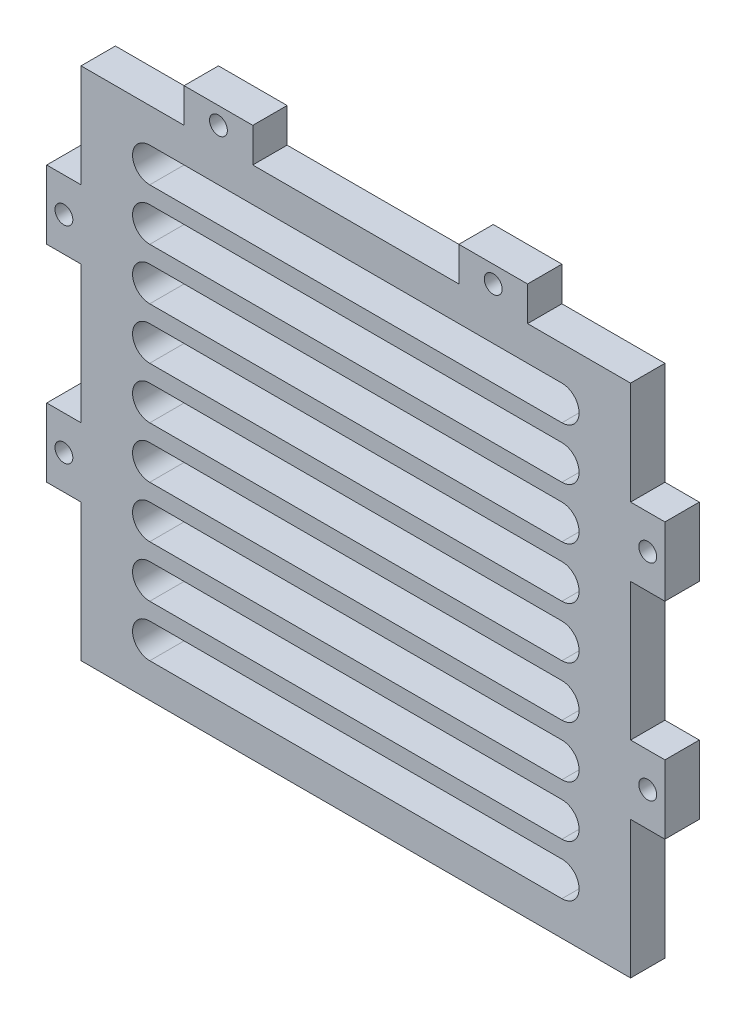
SolidWorks part; units mm, degrees
ref_plane "Front Plane" through (0, 0, 0) normal (0, 0, 1) x (1, 0, 0)
ref_plane "Top Plane" through (0, 0, 0) normal (0, 1, 0) x (1, 0, 0)
ref_plane "Right Plane" through (0, 0, 0) normal (1, 0, 0) x (0, 0, -1)
sketch "Sketch1" plane through (0, 0, 0) normal (0, 0, 1) x (1, 0, 0)
  line L1 (50.8, 39.9954) -> (-50.8, 39.9954)
  line L2 (50.8, 39.9954) -> (50.8, -55.2546)
  line L3 (50.8, -55.2546) -> (-50.8, -55.2546)
  line L4 (-50.8, 39.9954) -> (-50.8, -55.2546)
  line L5 (0, -55.2546) -> (0, 0) construction
  line L6 (50.8, -55.2546) -> (50.8, -29.8546) construction
  line L7 (-31.75, 39.9954) -> (-63.5, 39.9954) construction
  line L8 (-50.8, -55.2546) -> (-57.15, -55.2546) construction
extrude "Boss-Extrude1" add sketch "Sketch1" along normal blind 6.35
sketch "Sketch2" plane through (0, 0, 6.35) normal (0, 0, 1) x (1, 0, 0)
  line L0 (50.8, 39.9954) -> (-50.8, 39.9954) construction
  line L1 (-31.75, 39.9954) -> (-19.05, 39.9954)
  line L2 (-31.75, 39.9954) -> (-31.75, 46.3454)
  line L3 (-31.75, 46.3454) -> (-19.05, 46.3454)
  line L4 (-19.05, 39.9954) -> (-19.05, 46.3454)
  line L5 (-19.05, 43.1704) -> (19.05, 43.1704) construction
  line L6 (19.05, 39.9954) -> (31.75, 39.9954)
  line L7 (19.05, 39.9954) -> (19.05, 46.3454)
  line L8 (19.05, 46.3454) -> (31.75, 46.3454)
  line L9 (31.75, 39.9954) -> (31.75, 46.3454)
  line L10 (0, 43.1704) -> (0, 0) construction
  line L11 (-31.75, 46.3454) -> (-19.05, 39.9954) construction
  line L12 (19.05, 46.3454) -> (31.75, 39.9954) construction
  line L13 (-19.05, 46.3454) -> (-19.05, 39.9954) construction
  line L14 (-50.8, 39.9954) -> (-50.8, -55.2546) construction
  line L15 (-50.8, 20.9454) -> (-57.15, 20.9454)
  line L16 (-50.8, 20.9454) -> (-50.8, 8.2454)
  line L17 (-50.8, 8.2454) -> (-57.15, 8.2454)
  line L18 (-57.15, 20.9454) -> (-57.15, 8.2454)
  line L19 (50.8, -55.2546) -> (50.8, 39.9954) construction
  line L20 (50.8, 20.9454) -> (57.15, 20.9454)
  line L21 (50.8, 20.9454) -> (50.8, 8.2454)
  line L22 (50.8, 8.2454) -> (57.15, 8.2454)
  line L23 (57.15, 20.9454) -> (57.15, 8.2454)
  line L24 (-57.15, 20.9454) -> (-50.8, 8.2454) construction
  line L25 (50.8, 20.9454) -> (57.15, 8.2454) construction
  line L26 (50.8, 20.9454) -> (57.15, 20.9454) construction
  line L27 (-57.15, -17.1546) -> (-50.8, -29.8546) construction
  line L28 (-50.8, -17.1546) -> (-57.15, -17.1546)
  line L29 (-50.8, -17.1546) -> (-50.8, -29.8546)
  line L30 (-50.8, -29.8546) -> (-57.15, -29.8546)
  line L31 (-57.15, -17.1546) -> (-57.15, -29.8546)
  line L32 (50.8, -17.1546) -> (57.15, -17.1546)
  line L33 (50.8, -17.1546) -> (50.8, -29.8546)
  line L34 (50.8, -29.8546) -> (57.15, -29.8546)
  line L35 (57.15, -17.1546) -> (57.15, -29.8546)
  line L36 (50.8, -17.1546) -> (57.15, -29.8546) construction
  line L37 (50.8, -29.8546) -> (57.15, -29.8546) construction
  circle A0 centre (-25.4, 43.1704) radius 1.651
  circle A1 centre (25.4, 43.1704) radius 1.651
  circle A2 centre (-53.975, 14.5954) radius 1.651
  circle A3 centre (53.975, 14.5954) radius 1.651
  circle A4 centre (-53.975, -23.5046) radius 1.651
  circle A5 centre (53.975, -23.5046) radius 1.651
  dimension "D3" = 3.302
  dimension "D1" = 12.7
  dimension "D2" = 6.35
extrude "Boss-Extrude2" add sketch "Sketch2" against normal up to surface (6.35 mm away) up to face at (0, -7.6296, 0)
sketch "Sketch3" plane through (0, 0, 6.35) normal (0, 0, 1) x (1, 0, 0)
  line L0 (0, 39.9954) -> (0, -55.2546) construction
  line L1 (19.05, 39.9954) -> (-19.05, 39.9954) construction
  line L2 (-50.8, -55.2546) -> (50.8, -55.2546) construction
  line L3 (-38.1, 30.4704) -> (38.1, 30.4704) construction
  line L4 (-38.1, 33.6454) -> (38.1, 33.6454)
  line L5 (-38.1, 27.2954) -> (38.1, 27.2954)
  arc A0 (-38.1, 33.6454) -> (-38.1, 27.2954) centre (-38.1, 30.4704) ccw
  arc A1 (38.1, 27.2954) -> (38.1, 33.6454) centre (38.1, 30.4704) ccw
  point P8 (0, 30.4704)
  dimension "D1" = 3.175
  dimension "D2" = 76.2
  dimension "D3" = 9.525
extrude "Cut-Extrude1" cut sketch "Sketch3" against normal through all
pattern_linear "LPattern1" count 9 spacing 9.525 along (0, -1, 0) of "Cut-Extrude1"
